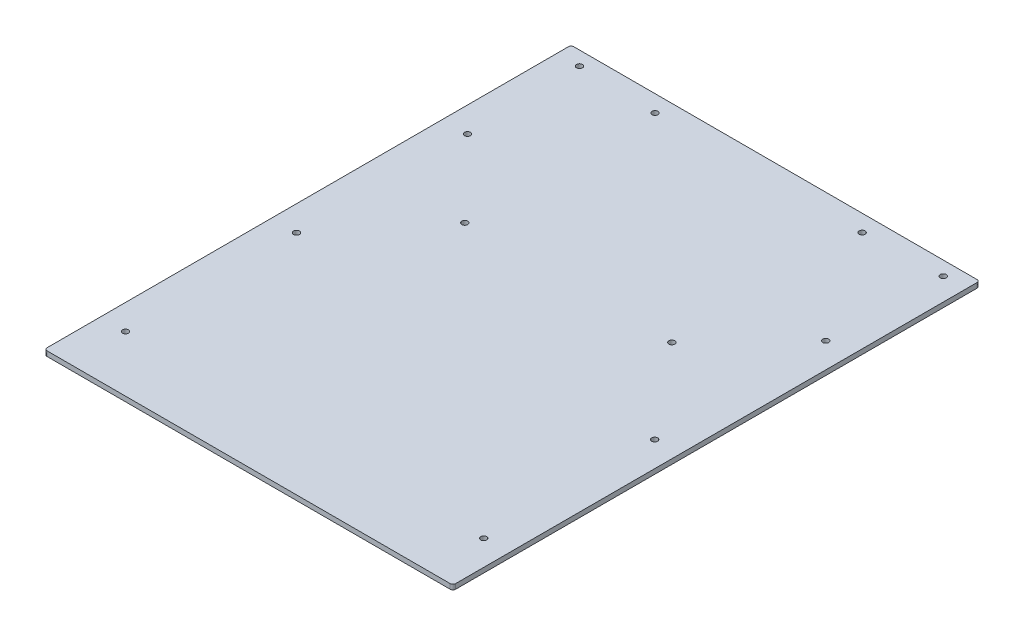
SolidWorks part; units mm, degrees
material "ABS PC"
ref_plane "Front Plane" through (0, 0, 0) normal (0, 0, 1) x (1, 0, 0)
ref_plane "Top Plane" through (0, 0, 0) normal (0, 1, 0) x (1, 0, 0)
ref_plane "Right Plane" through (0, 0, 0) normal (1, 0, 0) x (0, 0, -1)
sketch "Sketch1" plane through (0, 0, 0) normal (0, 1, 0) x (1, 0, 0)
  line L0 (231.775, 597.662) -> (231.775, 0) construction
  line L1 (0, 0) -> (463.55, 0)
  line L2 (0, 0) -> (0, 597.662)
  line L3 (0, 597.662) -> (463.55, 597.662)
  line L4 (463.55, 0) -> (463.55, 597.662)
  line L5 (28.575, 63.5) -> (28.575, 257.556) construction
  line L6 (28.575, 257.556) -> (28.575, 451.612) construction
  line L7 (434.975, 257.556) -> (434.975, 451.612) construction
  line L8 (434.975, 63.5) -> (434.975, 257.556) construction
  circle A0 centre (28.575, 63.5) radius 3.3782
  circle A1 centre (28.575, 257.556) radius 3.3782
  circle A2 centre (28.575, 451.612) radius 3.3782
  circle A3 centre (434.975, 451.612) radius 3.3782
  circle A4 centre (434.975, 257.556) radius 3.3782
  circle A5 centre (434.975, 63.5) radius 3.3782
  dimension "D3" = 6.7564
  dimension "D1" = 463.55
  dimension "D2" = 597.662
  dimension "D4" = 63.5
  dimension "D5" = 28.575
  dimension "D6" = 194.056
extrude "Boss-Extrude1" add sketch "Sketch1" along normal blind 5.588
fillet "Fillet1" radius 3.175 4 edges at (0, 2.794, -597.662) (463.55, 2.794, -597.662) (0, 2.794, 0) (463.55, 2.794, 0)
sketch "Sketch2" plane through (0, 5.588, 0) normal (0, 1, 0) x (1, 0, 0)
  line L0 (0, 581.787) -> (25.4, 581.787) construction
  line L1 (0, 594.487) -> (0, 3.175) construction
  line L2 (25.4, 581.787) -> (25.4, 597.662) construction
  line L3 (460.375, 597.662) -> (3.175, 597.662) construction
  line L4 (231.775, 597.662) -> (231.775, 0) construction
  line L5 (3.175, 0) -> (460.375, 0) construction
  line L6 (438.15, 581.787) -> (438.15, 597.662) construction
  line L7 (463.55, 581.787) -> (438.15, 581.787) construction
  circle A0 centre (25.4, 581.787) radius 3.3782
  circle A1 centre (438.15, 581.787) radius 3.3782
  dimension "D3" = 6.7564
  dimension "D1" = 15.875
  dimension "D2" = 25.4
extrude "Cut-Extrude1" cut sketch "Sketch2" against normal through all
sketch "Sketch3" plane through (0, 5.588, 0) normal (0, 1, 0) x (1, 0, 0)
  line L0 (231.775, 597.662) -> (231.775, 470.662) construction
  line L1 (460.375, 597.662) -> (3.175, 597.662) construction
  line L3 (114.3, 578.612) -> (349.25, 578.612) construction
  line L4 (114.3, 578.612) -> (114.3, 362.712) construction
  line L5 (114.3, 362.712) -> (349.25, 362.712) construction
  line L6 (349.25, 578.612) -> (349.25, 362.712) construction
  line L7 (114.3, 578.612) -> (349.25, 362.712) construction
  line L8 (114.3, 362.712) -> (349.25, 578.612) construction
  circle A0 centre (114.3, 578.612) radius 3.3782
  circle A1 centre (349.25, 578.612) radius 3.3782
  circle A2 centre (114.3, 362.712) radius 3.3782
  circle A3 centre (349.25, 362.712) radius 3.3782
  dimension "D3" = 6.7564
  dimension "D1" = 215.9
  dimension "D2" = 127
  dimension "D4" = 234.95
extrude "Cut-Extrude2" cut sketch "Sketch3" against normal through all
